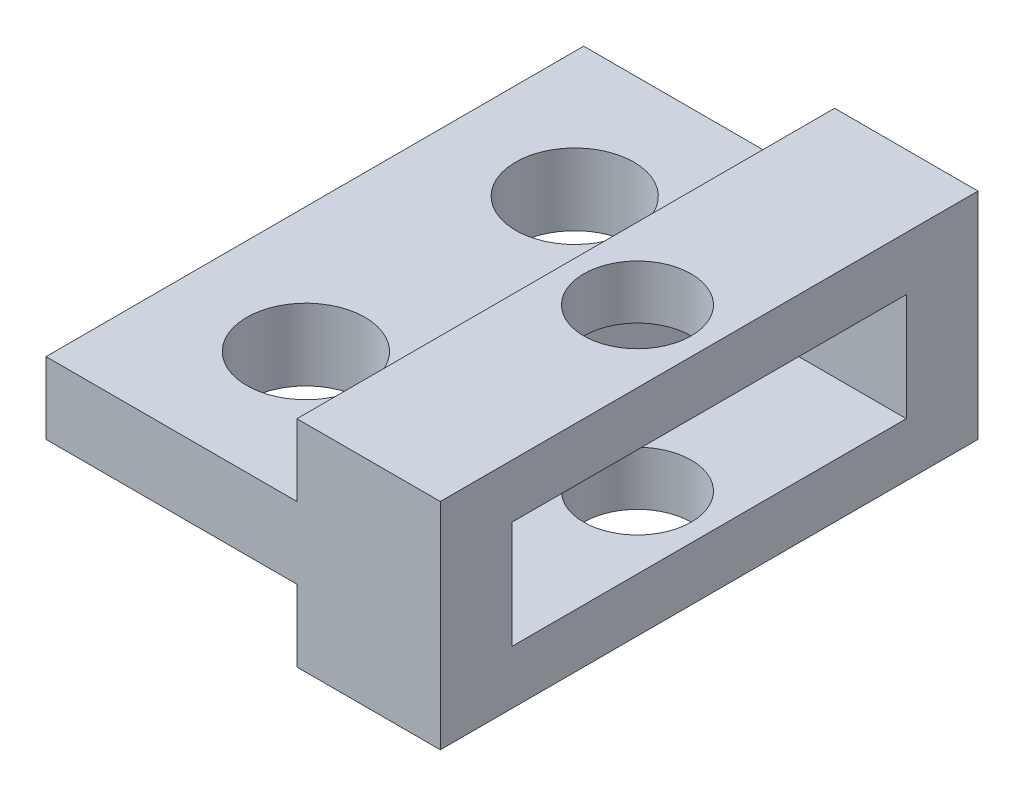
SolidWorks part; units mm, degrees
ref_plane "Front Plane" through (0, 0, 0) normal (0, 0, 1) x (1, 0, 0)
ref_plane "Top Plane" through (0, 0, 0) normal (0, 1, 0) x (1, 0, 0)
ref_plane "Right Plane" through (0, 0, 0) normal (1, 0, 0) x (0, 0, -1)
sketch "Sketch1" plane through (0, 0, 0) normal (0, 1, 0) x (1, 0, 0)
  line L1 (0, 0) -> (-11, 0)
  line L2 (0, 0) -> (0, 15)
  line L3 (0, 15) -> (-11, 15)
  line L4 (-11, 0) -> (-11, 15)
  dimension "D1" = 15
  dimension "D2" = 11
extrude "Boss-Extrude3" add sketch "Sketch1" along normal blind 2
sketch "Sketch2" plane through (0, 2, 0) normal (0, 1, 0) x (1, 0, 0)
  line L2 (-11, 0) -> (0, 0) construction
  line L3 (0, 15) -> (-4, 15)
  line L4 (0, 15) -> (0, 0)
  line L5 (0, 0) -> (-4, 0)
  line L6 (-4, 15) -> (-4, 0)
extrude "Boss-Extrude4" add sketch "Sketch2" along normal blind 2
sketch "Sketch3" plane through (0, 0, 0) normal (0, -1, 0) x (-1, 0, 0)
  line L0 (11, 0) -> (0, 0) construction
  line L1 (0, 15) -> (4, 15)
  line L2 (0, 15) -> (0, 0)
  line L3 (0, 0) -> (4, 0)
  line L4 (4, 15) -> (4, 0)
  dimension "D1" = 4
extrude "Boss-Extrude5" add sketch "Sketch3" along normal blind 2
sketch "Sketch4" plane through (0, 0, 0) normal (0, -1, 0) x (-1, 0, 0)
  line L0 (4, 0) -> (4, 15) construction
  line L1 (11, 0) -> (4, 0)
  line L2 (11, 0) -> (11, 7.5)
  line L4 (4, 0) -> (4, 7.5)
  circle A0 centre (7.5, 3.75) radius 1.65
  circle A1 centre (7.5, 11.25) radius 1.65
extrude "Cut-Extrude2" cut sketch "Sketch4" against normal blind 13 contours A1 | A0
sketch "Sketch6" plane through (0, 0, 0) normal (1, 0, 0) x (0, 0, -1)
  line L0 (0, 4) -> (15, 4) construction
  line L1 (15, -2) -> (13, -2)
  line L2 (15, -2) -> (15, 4)
  line L3 (15, 4) -> (13, 4)
  line L6 (0, -2) -> (2, -2)
  line L7 (0, -2) -> (0, 4)
  line L8 (0, 4) -> (2, 4)
  line L11 (13, -0.5) -> (2, -0.5)
  line L12 (13, -0.5) -> (13, 2.5)
  line L13 (13, 2.5) -> (2, 2.5)
  line L14 (2, -0.5) -> (2, 2.5)
  dimension "D1" = 2
  dimension "D2" = 2
  dimension "D3" = 1.5
  dimension "D4" = 3
extrude "Cut-Extrude4" cut sketch "Sketch6" against normal blind 3.8 contours L14 L11 L12 L13
sketch "Sketch7" plane through (0, -2, 0) normal (0, -1, 0) x (-1, 0, 0)
  circle A0 centre (2, 7.5) radius 1.5
extrude "Cut-Extrude5" cut sketch "Sketch7" against normal blind 17.8
